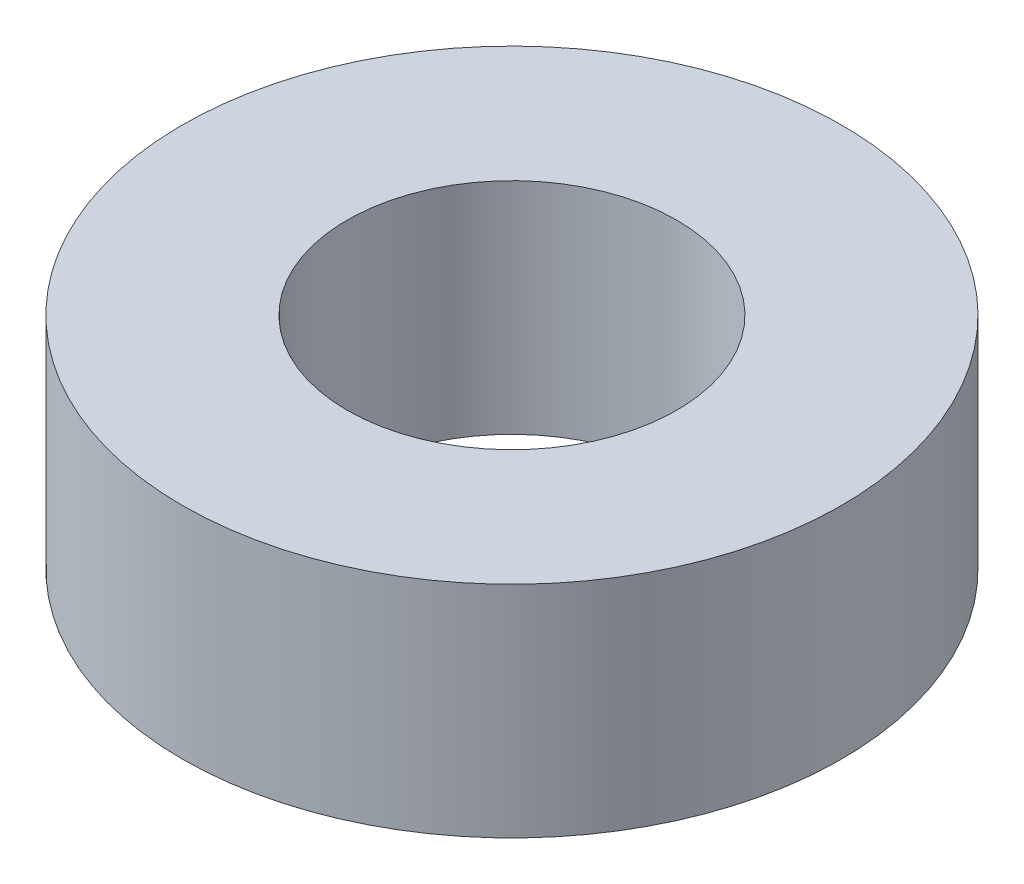
SolidWorks part; units mm, degrees
ref_plane "前视基准面" through (0, 0, 0) normal (0, 0, 1) x (1, 0, 0)
ref_plane "上视基准面" through (0, 0, 0) normal (0, 1, 0) x (1, 0, 0)
ref_plane "右视基准面" through (0, 0, 0) normal (1, 0, 0) x (0, 0, -1)
sketch "草图1" plane through (0, 0, 0) normal (0, 1, 0) x (1, 0, 0)
  circle A0 centre (-10.6643, 8.2406) radius 3
extrude "凸台-拉伸1" add sketch "草图1" along normal blind 2
sketch "草图3" plane through (0, 0, 0) normal (0, 1, 0) x (1, 0, 0)
  circle A0 centre (-10.6643, 8.2406) radius 1.5
extrude "切除-拉伸1" cut sketch "草图3" along normal through all
